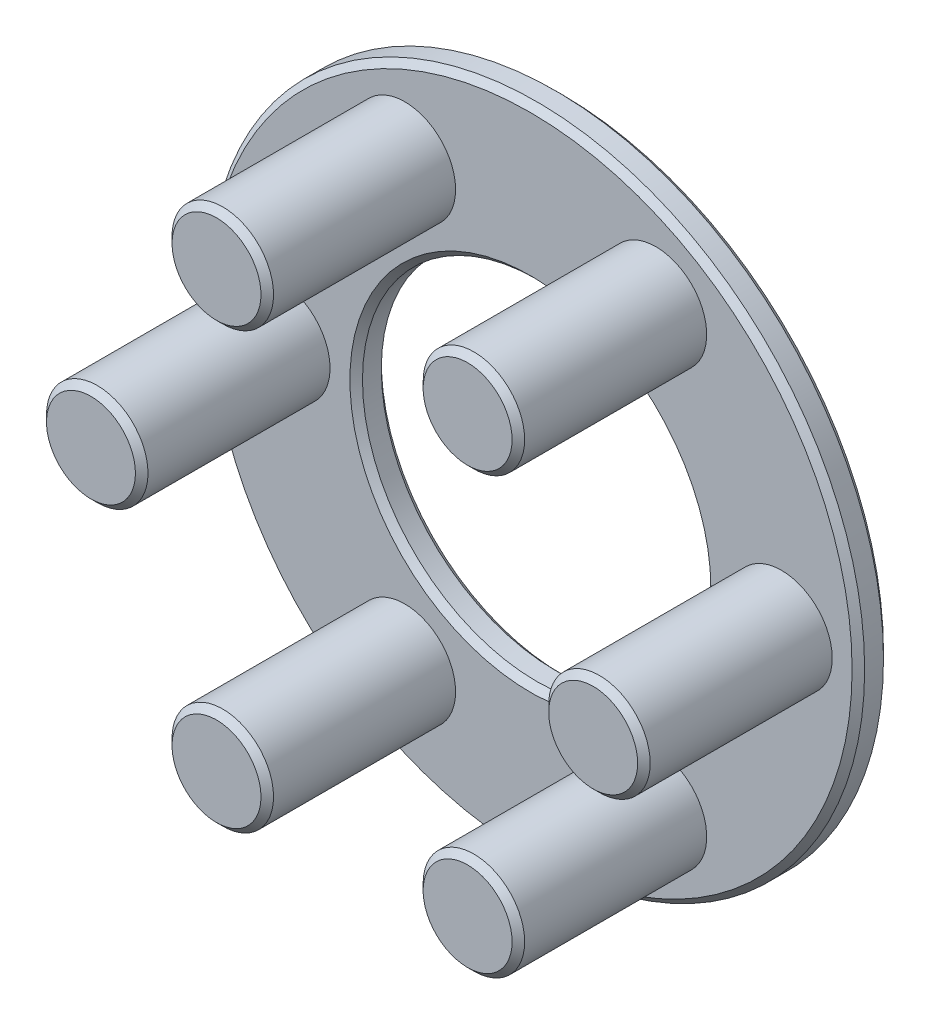
SolidWorks part; units mm, degrees
ref_plane "Front Plane" through (0, 0, 0) normal (0, 0, 1) x (1, 0, 0)
ref_plane "Top Plane" through (0, 0, 0) normal (0, 1, 0) x (1, 0, 0)
ref_plane "Right Plane" through (0, 0, 0) normal (1, 0, 0) x (0, 0, -1)
sketch "Sketch1" plane through (0, 0, 0) normal (0, 0, 1) x (1, 0, 0)
  line L0 (-31.35, 0) -> (-16.65, 0) construction
  circle A0 centre (0, 0) radius 16.65
  circle A1 centre (0, 0) radius 31.35
  circle A2 centre (0, 0) radius 24 construction
  point P7 (-24, 0)
  point P8 (-24, 0)
  dimension "D1" = 48
  dimension "D2" = 14.7
extrude "Boss-Extrude1" add sketch "Sketch1" against normal blind 3
sketch "Sketch2" plane through (0, 0, 0) normal (0, 0, 1) x (1, 0, 0)
  line L0 (16.65, 0) -> (31.35, 0) construction
  circle A0 centre (0, 0) radius 16.65 construction
  circle A1 centre (0, 0) radius 31.35 construction
  circle A2 centre (24, 0) radius 4.85
  dimension "D1" = 9.7
extrude "Boss-Extrude2" add sketch "Sketch2" along normal blind 18
pattern_circular "CirPattern1" count 6 over 360 about axis through (0, 0, 0) along (0, 0, 1) of "Boss-Extrude2"
chamfer "Chamfer1" distance 0.6 angle 45 10 edges at (-14.425, -24.9848, 18) (14.425, -24.9848, 18) (28.85, 0, 18) (14.425, 24.9848, 18) (-28.85, 0, 18) (-14.425, 24.9848, 18) (31.35, 0, -3) (31.35, 0, 0) (16.65, 0, -3) (16.65, 0, 0)
scale "Scale1" scale about centroid uniform scaling yes scale factor 0.4
